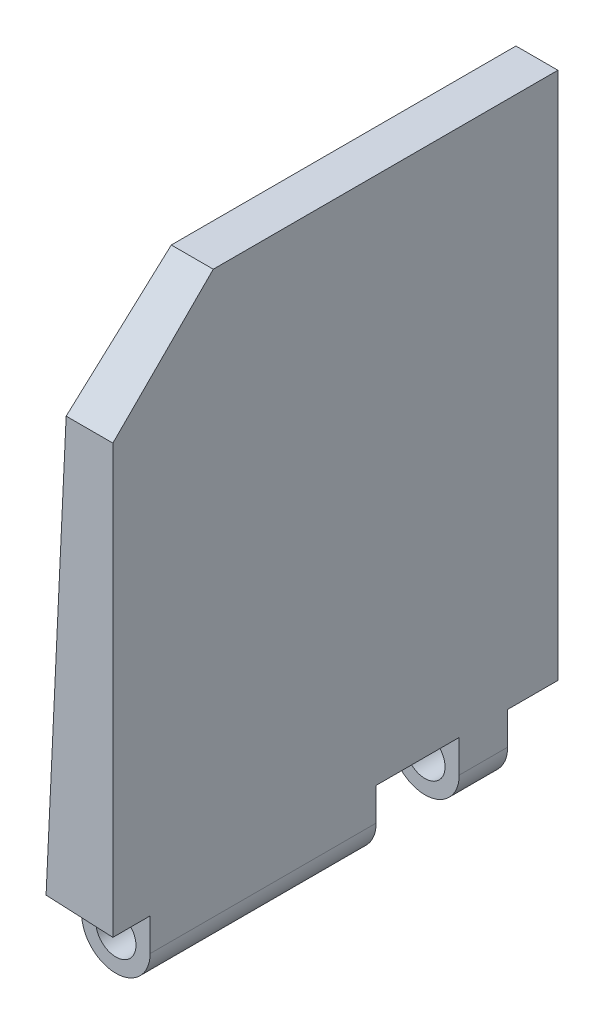
SolidWorks part; units mm, degrees
ref_plane "Front Plane" through (0, 0, 0) normal (0, 0, 1) x (1, 0, 0)
ref_plane "Top Plane" through (0, 0, 0) normal (0, 1, 0) x (1, 0, 0)
ref_plane "Right Plane" through (0, 0, 0) normal (1, 0, 0) x (0, 0, -1)
sketch "Sketch1" plane through (0, 0, 0) normal (0, 0, 1) x (1, 0, 0)
  line L0 (-7.6671, 148.3786) -> (-6.3289, 176.6901)
  line L1 (-4.2046, 176.6901) -> (-4.2046, 148.2968)
  line L2 (-6.3289, 176.6901) -> (-4.2046, 176.6901)
  arc A1 (-4.2046, 148.2968) -> (-7.6671, 148.3786) centre (-5.9368, 148.2968) cw
  dimension "D1" = 28.3933
  dimension "D2" = 2.706
  dimension "D3" = 2.1243
extrude "Extrude1" add sketch "Sketch1" against normal blind 22.52
sketch "Sketch2" plane through (-14.6477, 0.6924, 0) normal (-0.9989, 0.0472, 0) x (0, 0, 1)
  line L1 (-1.8847, 146.1189) -> (0, 146.1189)
  line L2 (-1.8847, 146.1189) -> (-1.8847, 149.5833)
  line L3 (-1.8847, 149.5833) -> (0, 149.5833)
  line L4 (0, 146.1189) -> (0, 149.5833)
  line L5 (0, 176.1942) -> (0, 147.8511) construction
  line L7 (-17.5249, 146.1189) -> (-13.3231, 146.1189)
  line L8 (-17.5249, 146.1189) -> (-17.5249, 149.5833)
  line L9 (-17.5249, 149.5833) -> (-13.3231, 149.5833)
  line L10 (-13.3231, 146.1189) -> (-13.3231, 149.5833)
  line L13 (-19.9768, 146.1189) -> (-22.52, 146.1189)
  line L14 (-19.9768, 146.1189) -> (-19.9768, 149.5833)
  line L15 (-19.9768, 149.5833) -> (-22.52, 149.5833)
  line L16 (-22.52, 146.1189) -> (-22.52, 149.5833)
  line L17 (-22.52, 176.1942) -> (-22.52, 147.8511) construction
  line L18 (-22.52, 146.1189) -> (0, 146.1189) construction
  line L19 (-3.8292, 147.8511) -> (-10.3456, 147.8511) construction
  line L20 (-22.52, 147.8511) -> (0, 147.8511) construction
extrude "Cut-Extrude1" cut sketch "Sketch2" against normal through all
sketch "Sketch3" plane through (0, 0, -1.8847) normal (0, 0, 1) x (1, 0, 0)
  circle A1 centre (-5.9368, 148.2968) radius 1.016
  arc A2 (-7.6671, 148.3786) -> (-4.2046, 148.2968) centre (-5.9368, 148.2968) ccw construction
  dimension "D1" = 2.032
extrude "Cut-Extrude2" cut sketch "Sketch3" against normal through all
chamfer "Chamfer1" distance 5.08 angle 45 1 edges at (-5.2667, 176.6901, 0)
